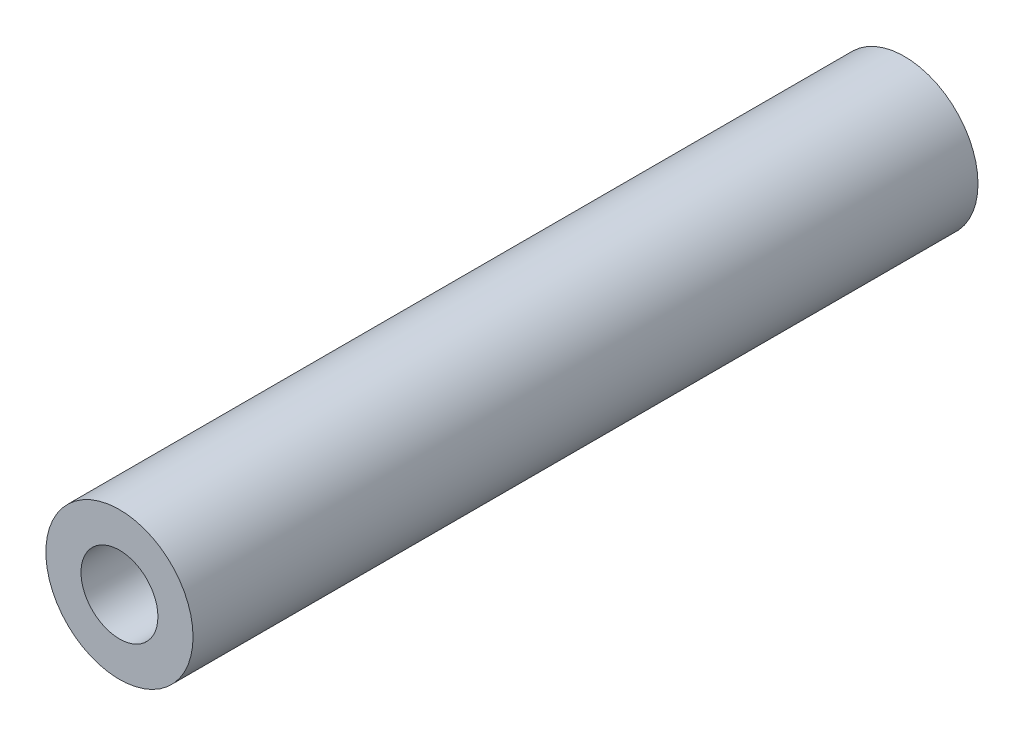
SolidWorks part; units mm, degrees
material "6061-T6 (SS)"
ref_plane "Front Plane" through (0, 0, 0) normal (0, 0, 1) x (1, 0, 0)
ref_plane "Top Plane" through (0, 0, 0) normal (0, 1, 0) x (1, 0, 0)
ref_plane "Right Plane" through (0, 0, 0) normal (1, 0, 0) x (0, 0, -1)
sketch "Sketch1" plane through (0, 0, 0) normal (0, 0, 1) x (1, 0, 0)
  circle A0 centre (0, 0) radius 4.7625
  circle A1 centre (0, 0) radius 2.4892
  dimension "D1" = 9.525
  dimension "D2" = 4.9784
extrude "Boss-Extrude1" add sketch "Sketch1" along normal blind 50.8
